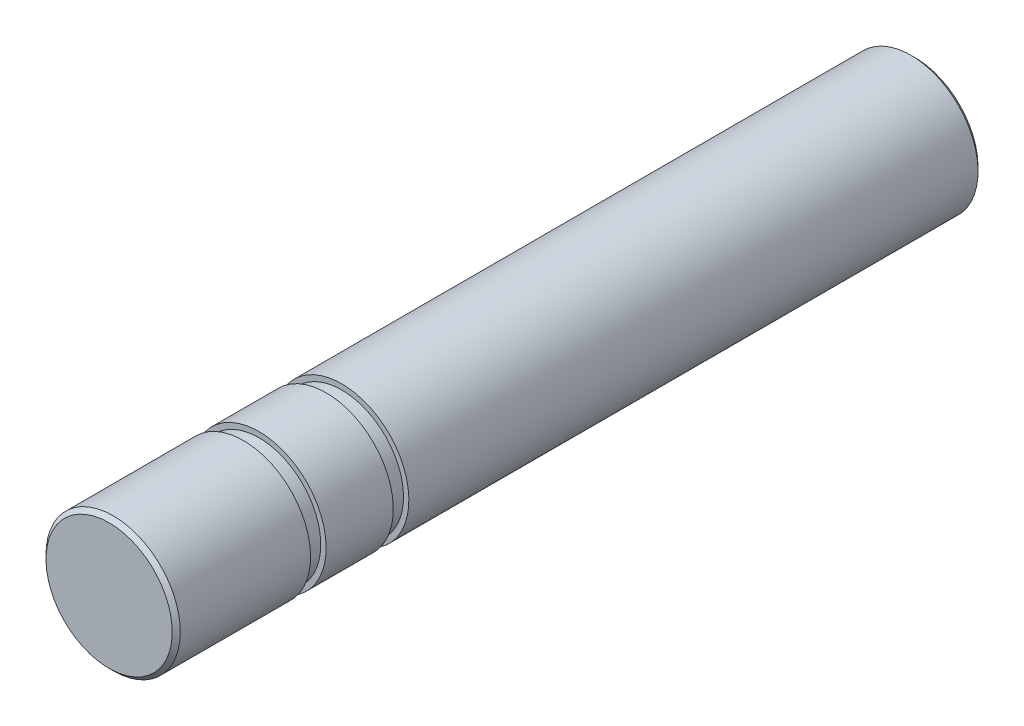
SolidWorks part; units mm, degrees
ref_plane "Front Plane" through (0, 0, 0) normal (0, 0, 1) x (1, 0, 0)
ref_plane "Top Plane" through (0, 0, 0) normal (0, 1, 0) x (1, 0, 0)
ref_plane "Right Plane" through (0, 0, 0) normal (1, 0, 0) x (0, 0, -1)
sketch "Sketch1" plane through (0, 0, 0) normal (1, 0, 0) x (0, 0, -1)
  line L0 (19.05, 0) -> (-19.05, 0) construction
  line L1 (-19.05, 3.175) -> (-19.05, -3.175) construction
  line L2 (-19.05, 3.175) -> (-12.7, 3.175) construction
  line L4 (-12.7, 3.175) -> (-11.9634, 3.175) construction
  line L5 (-11.9634, 3.175) -> (-8.7884, 3.175) construction
  line L6 (-8.7884, 3.175) -> (-8.0518, 3.175) construction
  line L7 (-12.7, -2.921) -> (-12.7, 2.921) construction
  point P4 (0, 0)
  point P7 (-19.05, 0)
  point P15 (-12.7, 0)
  dimension "Diameter" = 6.35
  dimension "Length" = 38.1
  dimension "End to Groove" = 6.35
  dimension "Groove Width" = 0.7366
  dimension "Groove to Groove" = 3.175
  dimension "D1" = 0.7366
  dimension "Groove Diameter" = 5.842
sketch "Sketch3" plane through (0, 0, 0) normal (1, 0, 0) x (0, 0, -1)
  line L0 (-19.05, 3.175) -> (-19.05, 0)
  line L1 (-19.05, 0) -> (19.05, 0)
  line L2 (19.05, 0) -> (19.05, 3.175)
  line L4 (-19.05, 3.175) -> (-12.7, 3.175)
  line L5 (-12.7, 3.175) -> (-12.7, 2.921)
  line L6 (-12.7, 2.921) -> (-11.9634, 2.921)
  line L7 (-11.9634, 2.921) -> (-11.9634, 3.175)
  line L8 (-11.9634, 3.175) -> (-8.7884, 3.175)
  line L9 (-8.7884, 3.175) -> (-8.7884, 2.921)
  line L10 (-8.7884, 2.921) -> (-8.0518, 2.921)
  line L11 (-8.0518, 2.921) -> (-8.0518, 3.175)
  line L12 (-8.0518, 3.175) -> (19.05, 3.175)
revolve "Revolve1" add sketch "Sketch3" angle 360 about L1
sketch "Sketch5" plane through (0, 0, 0) normal (0, 0, 1) x (1, 0, 0)
  line L0 (-3.175, 0) -> (3.175, 0) construction
  line L1 (0, -3.175) -> (0, 3.175) construction
  point P5 (0, 0)
  point P9 (0, 0)
  point P10 (0, 3.175)
  dimension "Diameter" = 6.35
  dimension "D2" = 6.35
sketch "Sketch6" plane through (0, 0, 0) normal (1, 0, 0) x (0, 0, -1)
  line L0 (19.05, 0) -> (-19.05, 0) construction
  line L1 (-12.7, -2.921) -> (-12.7, 2.921) construction
  line L4 (-19.05, -3.175) -> (19.05, -3.175) construction
  line L6 (-12.7, 3.175) -> (-12.7, -3.175) construction
  line L7 (-11.9634, 3.175) -> (-11.9634, -3.175) construction
  point P0 (-12.7, 3.175)
  point P3 (-7.2492, 0)
  point P4 (0, 0)
  point P7 (-19.05, 3.175)
  point P9 (7.2492, 0)
  point P11 (-12.7, 0)
  point P12 (-3.3155, 0)
  point P13 (5.4236, 0)
  point P14 (19.05, 3.175)
  point P18 (-12.7, 2.921)
  point P19 (-19.05, -3.175)
  point P20 (19.05, -3.175)
  point P25 (-12.7, -2.921)
  point P26 (-11.9634, 3.175)
  point P28 (-8.7884, 3.175)
  point P30 (-8.0518, 3.175)
  point P37 (-12.7, -3.175)
  point P38 (-11.9634, -3.175)
  dimension "Length" = 38.1
  dimension "D1" = 11.8008
  dimension "D2" = 11.8008
  dimension "D3" = 15.7345
  dimension "D4" = 13.6264
  dimension "D5" = 6.35
chamfer "Chamfer1" distance 0.1905 angle 45 2 edges at (0, -3.175, -19.05) (0, -3.175, 19.05)
equation "\"Diameter@Sketch5\" = \"Diameter@Sketch1\""
equation "\"D2@Sketch5\" = \"Diameter@Sketch5\""
equation "\"Length@Sketch6\"=\"Length@Sketch1\""
equation "\"D1@Sketch6\"=(\"End to Groove@Sketch1\" + \"Groove to Groove@Sketch1\" + \"Groove Width@Sketch1\")*1.15"
equation "\"D2@Sketch6\"=\"D1@Sketch6\""
equation "\"D3@Sketch6\"=\"D1@Sketch6\"*4/3"
equation "\"D4@Sketch6\"=\"D1@Sketch6\"/(TAN(0.5236rad)*2)*4/3"
equation "\"D1@Chamfer1\"=\"Length@Sketch1\"*0.005"
equation "\"D1@Sketch1\"=\"Groove Width@Sketch1\""
equation "\"D5@Sketch6\"=\"Diameter@Sketch1\""
